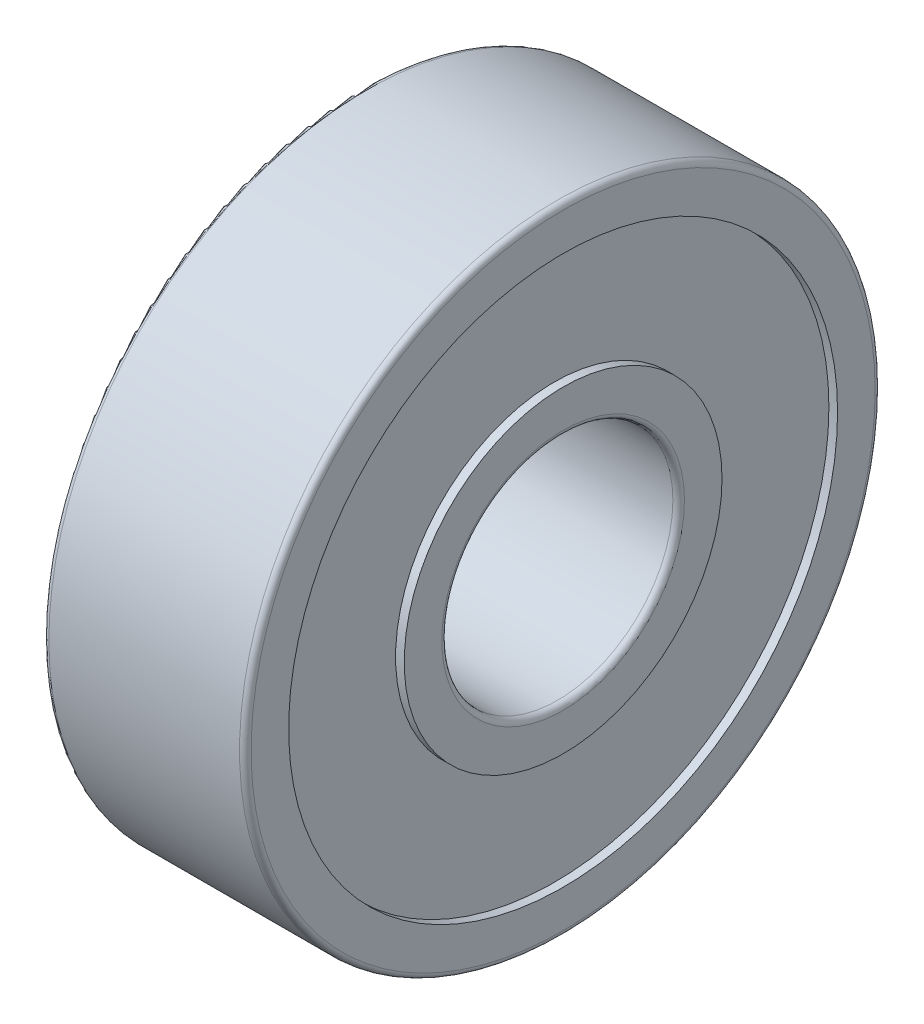
SolidWorks part; units mm, degrees
material "Plain Carbon Steel"
ref_plane "Front Plane" through (0, 0, 0) normal (0, 0, 1) x (1, 0, 0)
ref_plane "Top Plane" through (0, 0, 0) normal (0, 1, 0) x (1, 0, 0)
ref_plane "Right Plane" through (0, 0, 0) normal (1, 0, 0) x (0, 0, -1)
sketch "Sketch1" plane through (0, 0, 0) normal (0, 0, 1) x (1, 0, 0)
  line L0 (3.5, 4) -> (-3.5, 4)
  line L1 (-3.5, 4) -> (-3.5, 5.5)
  line L2 (-3.5, 5.5) -> (-3.2, 5.5)
  line L3 (-3.2, 5.5) -> (-3.2, 9.5)
  line L4 (-3.2, 9.5) -> (-3.5, 9.5)
  line L5 (-3.5, 9.5) -> (-3.5, 11)
  line L6 (-3.5, 11) -> (3.5, 11)
  line L7 (0, 11) -> (0, 4) construction
  line L8 (3.5, 9.5) -> (3.5, 11)
  line L9 (3.2, 9.5) -> (3.5, 9.5)
  line L10 (3.2, 5.5) -> (3.2, 9.5)
  line L11 (3.5, 5.5) -> (3.2, 5.5)
  line L12 (3.5, 4) -> (3.5, 5.5)
  line L13 (0, 0) -> (-4.3663, 0) construction
  dimension "D1" = 8
  dimension "D2" = 22
  dimension "D3" = 7
  dimension "D4" = 1.5
  dimension "D5" = 1.5
  dimension "D6" = 0.3
revolve "Revolve1" add sketch "Sketch1" angle 360 about L13
fillet "Fillet1" radius 0.2 4 edges at (-3.5, 0, -11) (3.5, 0, -11) (-3.5, 0, -4) (3.5, 0, -4)
